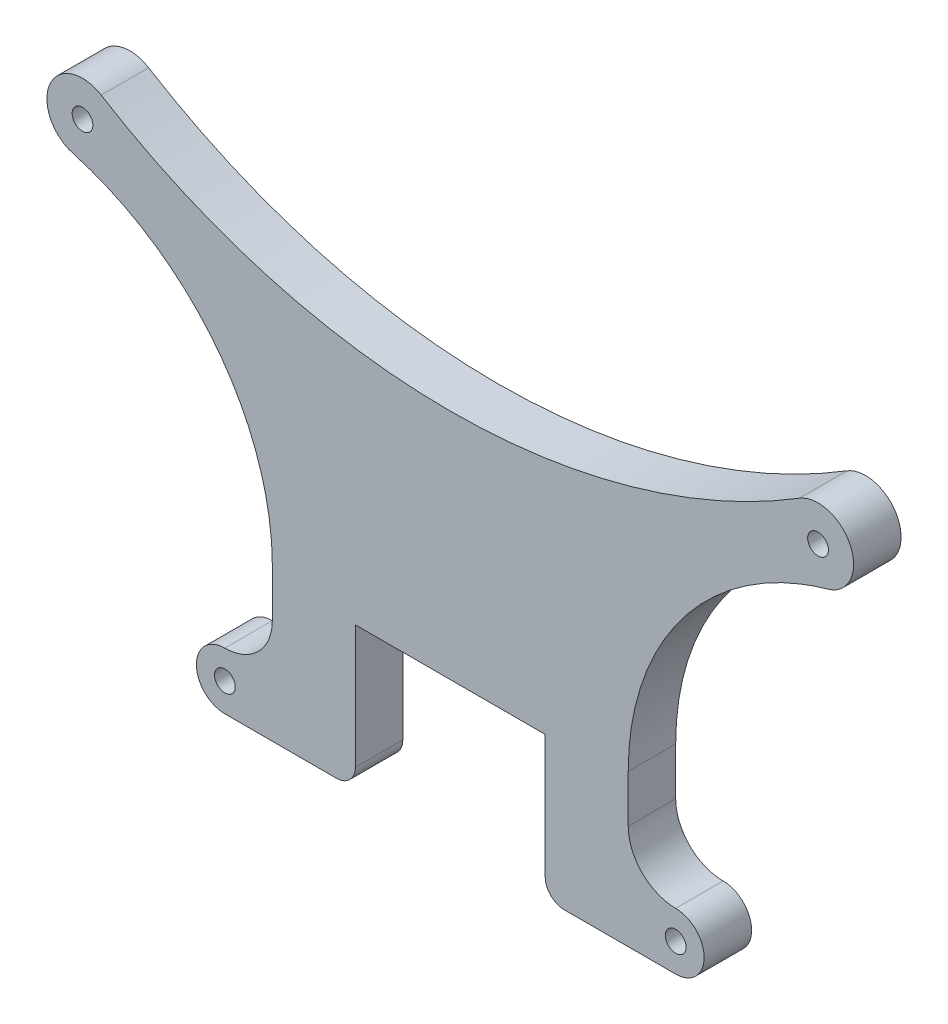
SolidWorks part; units mm, degrees
ref_plane "Front Plane" through (0, 0, 0) normal (0, 0, 1) x (1, 0, 0)
ref_plane "Top Plane" through (0, 0, 0) normal (0, 1, 0) x (1, 0, 0)
ref_plane "Right Plane" through (0, 0, 0) normal (1, 0, 0) x (0, 0, -1)
sketch "Sketch1" plane through (0, 0, 0) normal (0, 0, 1) x (1, 0, 0)
  line L0 (0, 45.085) -> (0, -57.25) construction
  line L1 (12.7, 0) -> (-12.7, 0)
  line L2 (-12.7, 0) -> (-12.7, -16.51)
  line L3 (-15.24, -19.05) -> (-30.1625, -19.05)
  line L4 (-49.2125, 45.085) -> (6.4719, 45.085) construction
  line L5 (-23.8125, -5.08) -> (-23.8125, 1.27)
  line L6 (12.7, 0) -> (12.7, -16.51)
  line L7 (15.24, -19.05) -> (30.1625, -19.05)
  line L8 (23.8125, -5.08) -> (23.8125, 1.27)
  arc A0 (-30.1625, -19.05) -> (-30.1625, -11.43) centre (-30.1625, -15.24) cw
  arc A1 (-46.7103, 44.3747) -> (-50.503, 35.7382) centre (-49.2125, 40.3225) ccw
  arc A2 (46.7103, 44.3747) -> (-46.7103, 44.3747) centre (0, 120.0186) cw
  arc A3 (-30.1625, -11.43) -> (-23.8125, -5.08) centre (-30.1625, -5.08) ccw
  circle A4 centre (-49.2125, 40.3225) radius 1.3891
  circle A5 centre (-30.1625, -15.24) radius 1.3891
  circle A6 centre (30.1625, -15.24) radius 1.3891
  arc A7 (30.1625, -19.05) -> (30.1625, -11.43) centre (30.1625, -15.24) ccw
  arc A8 (30.1625, -11.43) -> (23.8125, -5.08) centre (30.1625, -5.08) cw
  circle A9 centre (49.2125, 40.3225) radius 1.3891
  arc A10 (46.7103, 44.3747) -> (50.503, 35.7382) centre (49.2125, 40.3225) cw
  arc A11 (-15.24, -19.05) -> (-12.7, -16.51) centre (-15.24, -16.51) ccw
  arc A12 (15.24, -19.05) -> (12.7, -16.51) centre (15.24, -16.51) cw
  ellipse E0 centre (-60.8178, 1.27) end of major axis (-23.8125, 1.27) minor radius 35.8906 (-50.503, 35.7382) -> (-23.8125, 1.27) cw
  ellipse E1 centre (60.8178, 1.27) end of major axis (97.8232, 1.27) minor radius 35.8906 (50.503, 35.7382) -> (23.8125, 1.27) ccw
  point P9 (-49.2125, 40.3225)
  point P14 (0, 31.115)
  point P28 (0, 0)
  point P47 (-12.7, -19.05)
  point P50 (12.7, -19.05)
  dimension "D4" = 3.81
  dimension "D7" = 9.525
  dimension "D9" = 6.35
  dimension "D12" = 2.7781
  dimension "D13" = 2.7781
  dimension "D14" = 2.54
  dimension "D15" = 2.54
  dimension "D1" = 12.7
  dimension "D2" = 19.05
  dimension "D3" = 17.4625
  dimension "D5" = 19.05
  dimension "D6" = 55.5625
  dimension "D8" = 13.97
  dimension "D10" = 6.35
  dimension "D11" = 60.8178
extrude "Boss-Extrude1" add sketch "Sketch1" along normal blind 6.35
